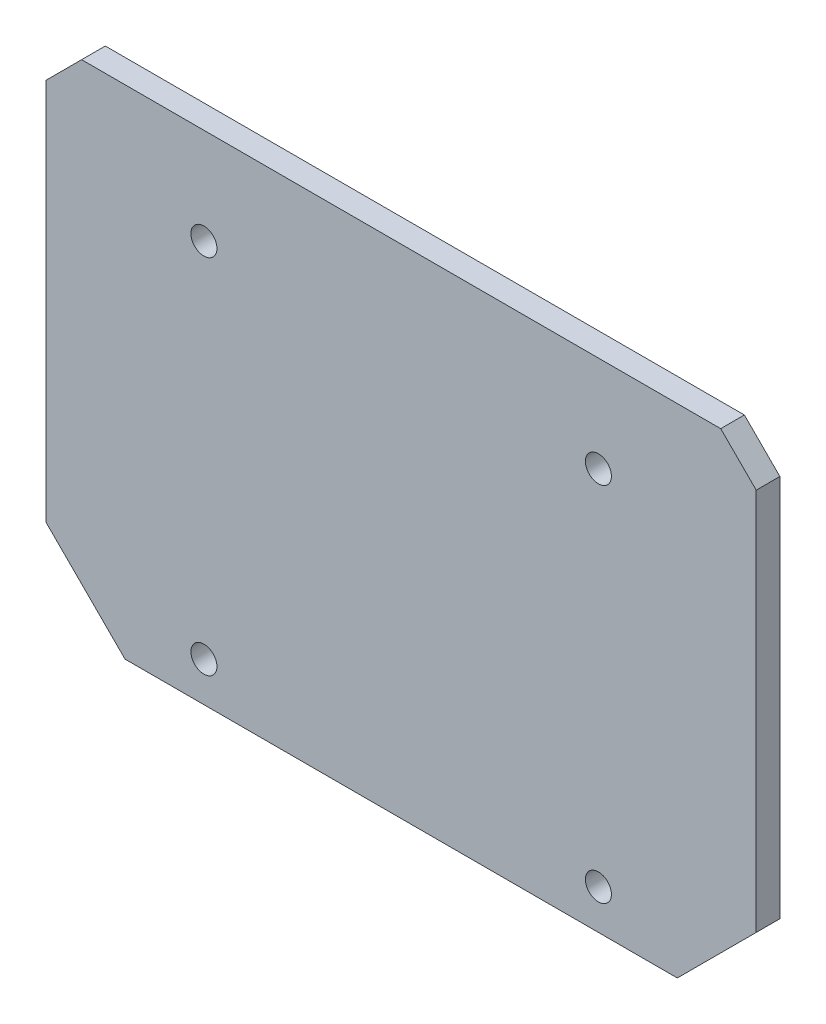
SolidWorks part; units mm, degrees
ref_plane "Front Plane" through (0, 0, 0) normal (0, 0, 1) x (1, 0, 0)
ref_plane "Top Plane" through (0, 0, 0) normal (0, 1, 0) x (1, 0, 0)
ref_plane "Right Plane" through (0, 0, 0) normal (1, 0, 0) x (0, 0, -1)
sketch "Sketch1" plane through (0, 0, 0) normal (0, 0, 1) x (1, 0, 0)
  line L0 (0.5528, 47.78) -> (20.5528, 47.78) construction
  line L1 (-49.4472, 47.78) -> (-29.4472, 47.78) construction
  line L2 (-49.4472, 47.78) -> (-49.4472, -25.43) construction
  line L3 (-49.4472, -25.43) -> (-29.4472, -25.43) construction
  line L4 (-29.4472, 47.78) -> (-29.4472, -25.43) construction
  line L5 (0.5528, 47.78) -> (0.5528, -25.43) construction
  line L6 (0.5528, -25.43) -> (20.5528, -25.43) construction
  line L7 (20.5528, 47.78) -> (20.5528, -25.43) construction
  line L8 (0.5528, -30.43) -> (20.5528, -30.43) construction
  line L9 (-49.4472, -30.43) -> (-29.4472, -30.43) construction
  line L10 (-49.4472, -30.43) -> (-49.4472, -103.64) construction
  line L11 (-49.4472, -103.64) -> (-29.4472, -103.64) construction
  line L12 (-29.4472, -30.43) -> (-29.4472, -103.64) construction
  line L13 (0.5528, -30.43) -> (0.5528, -103.64) construction
  line L14 (0.5528, -103.64) -> (20.5528, -103.64) construction
  line L15 (20.5528, -30.43) -> (20.5528, -103.64) construction
  line L16 (-59.4472, 47.78) -> (-49.4472, 57.78)
  line L17 (-49.4472, 57.78) -> (20.5528, 57.78)
  line L18 (-59.4472, 47.78) -> (-59.4472, -0.7692)
  line L19 (-49.4472, -113.64) -> (20.5528, -113.64)
  line L21 (20.5528, 57.78) -> (30.5528, 47.78)
  line L22 (30.5528, -103.64) -> (20.5528, -113.64)
  line L23 (-59.4472, -103.64) -> (-49.4472, -113.64)
  line L24 (-54.4472, 52.78) -> (-54.4472, -62.7481) construction
  line L25 (-54.4472, -50.5907) -> (-54.9472, -50.5907)
  line L26 (-54.4472, -50.5907) -> (-54.4472, -5.2692)
  line L27 (-54.4472, -5.2692) -> (-54.9472, -5.2692)
  line L29 (-59.4472, -0.7692) -> (-54.9472, -5.2692)
  line L30 (-54.9472, -50.5907) -> (-59.4472, -55.0907)
  line L31 (-59.4472, -55.0907) -> (-59.4472, -103.64)
  line L32 (-14.4472, 57.78) -> (-14.4472, -113.64) construction
  line L33 (30.5528, -55.0907) -> (30.5528, -103.64)
  line L34 (25.5528, -50.5907) -> (26.0528, -50.5907)
  line L35 (26.0528, -50.5907) -> (30.5528, -55.0907)
  line L36 (25.5528, -50.5907) -> (25.5528, -5.2692)
  line L37 (30.5528, 47.78) -> (30.5528, -0.7692)
  line L38 (30.5528, -0.7692) -> (26.0528, -5.2692)
  line L39 (25.5528, -5.2692) -> (26.0528, -5.2692)
  line L40 (-39.4472, 57.78) -> (-39.4472, 52.78) construction
  line L41 (10.5528, 57.78) -> (10.5528, 52.78) construction
  line L42 (-54.4472, -27.93) -> (25.5528, -27.93) construction
  line L43 (-29.4472, 11.175) -> (0.5528, 11.175) construction
  line L45 (-29.4472, 21.175) -> (-29.4472, 1.175)
  line L47 (-26.4472, 21.175) -> (-26.4472, 1.175)
  line L49 (0.5528, 21.175) -> (0.5528, 1.175)
  line L51 (-2.4472, 21.175) -> (-2.4472, 1.175)
  line L60 (-29.4472, 1.175) -> (-26.4472, 1.175)
  line L61 (-29.4472, 21.175) -> (-26.4472, 21.175)
  line L62 (-2.4472, 21.175) -> (0.5528, 21.175)
  line L63 (-2.4472, 1.175) -> (0.5528, 1.175)
  line L64 (-29.4472, 21.175) -> (0.5528, 21.175) construction
  line L66 (-29.4472, 1.175) -> (0.5528, 1.175) construction
  line L83 (-26.4472, -39.0454) -> (-2.4472, -39.0454)
  line L84 (-26.4472, -39.0454) -> (-26.4472, -16.8145)
  line L85 (-26.4472, -16.8145) -> (-2.4472, -16.8145)
  line L86 (-2.4472, -39.0454) -> (-2.4472, -16.8145)
  line L87 (-26.4472, -39.0454) -> (-2.4472, -16.8145) construction
  line L88 (-26.4472, -16.8145) -> (-2.4472, -39.0454) construction
  circle A0 centre (-39.4472, 52.78) radius 1.65
  circle A1 centre (10.5528, 52.78) radius 1.65
  circle A2 centre (10.5528, -108.64) radius 1.65
  circle A3 centre (-39.4472, -108.64) radius 1.65
  circle A4 centre (10.5528, -62.7481) radius 1.65
  circle A5 centre (-39.4472, -62.7481) radius 1.65
  point P16 (-59.4472, 57.78)
  point P17 (30.5528, -113.64)
  point P18 (-59.4472, -113.64)
  point P19 (30.5528, 57.78)
  point P28 (-59.4472, -27.93)
  point P35 (-59.4472, -5.2692)
  point P37 (-59.4472, -50.5907)
  point P41 (-54.6972, -50.5907)
  point P43 (25.8028, -50.5907)
  point P76 (-14.4472, -27.93)
  dimension "D17" = 3.3
  dimension "D23" = 3.3
  dimension "D28" = 3.3
  dimension "D1" = 30
  dimension "D2" = 30
  dimension "D3" = 20
  dimension "D4" = 20
  dimension "D5" = 20
  dimension "D6" = 20
  dimension "D7" = 20
  dimension "D8" = 10
  dimension "D9" = 10
  dimension "D10" = 20
  dimension "D11" = 73.21
  dimension "D12" = 73.21
  dimension "D13" = 73.21
  dimension "D14" = 73.21
  dimension "D15" = 5
  dimension "D16" = 10
  dimension "D18" = 20
  dimension "D24" = 10
  dimension "D29" = 30
  dimension "D25" = 10
extrude "Boss-Extrude2" add sketch "Sketch1" along normal blind 3
sketch "Sketch3" plane through (0, 0, 3) normal (0, 0, 1) x (1, 0, 0)
  line L0 (-54.4472, -50.5907) -> (-54.9472, -50.5907) construction
  line L1 (42.5365, 75.5226) -> (-60.3392, 75.5226)
  line L2 (42.5365, 75.5226) -> (42.5365, -50.5907)
  line L3 (42.5365, -50.5907) -> (-60.3392, -50.5907)
  line L4 (-60.3392, 75.5226) -> (-60.3392, -50.5907)
extrude "Cut-Extrude1" cut sketch "Sketch3" against normal blind 10
